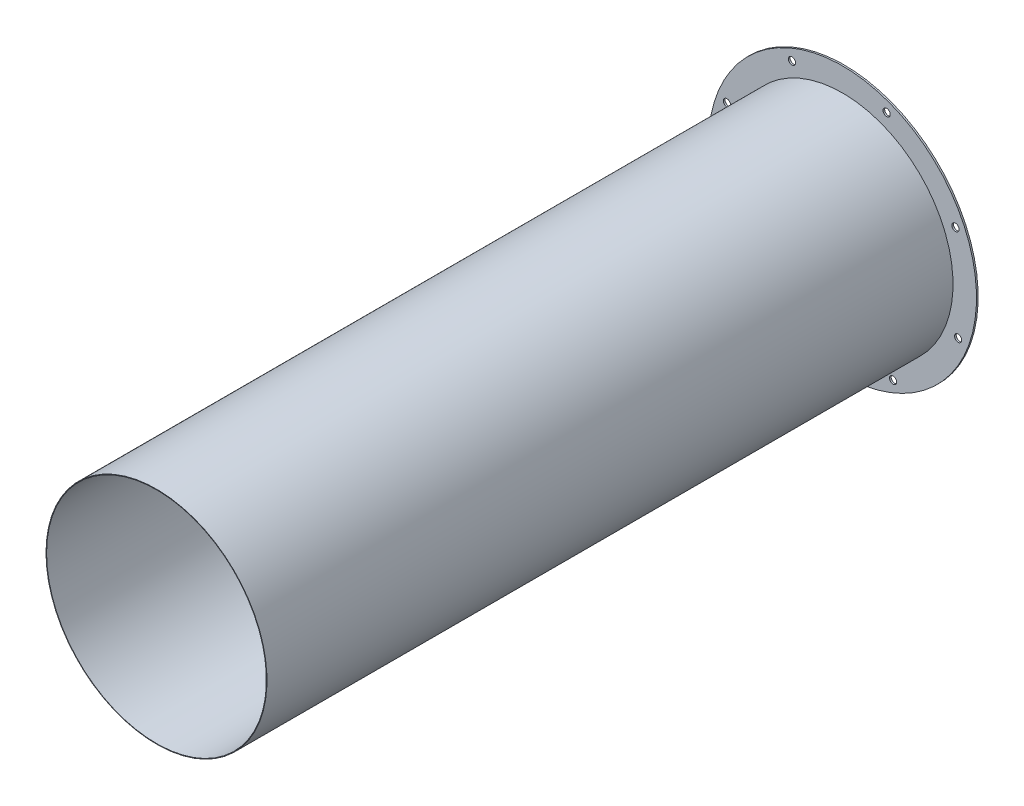
SolidWorks part; units mm, degrees
material "Galvanized Steel"
ref_plane "Front Plane" through (0, 0, 0) normal (0, 0, 1) x (1, 0, 0)
ref_plane "Top Plane" through (0, 0, 0) normal (0, 1, 0) x (1, 0, 0)
ref_plane "Right Plane" through (0, 0, 0) normal (1, 0, 0) x (0, 0, -1)
sketch "Sketch1" plane through (0, 0, 0) normal (0, 0, 1) x (1, 0, 0)
  circle A0 centre (0, 0) radius 200
  dimension "D1" = 400
extrude "Extrude-Thin1" add sketch "Sketch1" along normal mid plane 1245 thin thin type one direction reverse wall 1
sketch "Sketch2" plane through (0, 0, -622.5) normal (0, 0, -1) x (-1, 0, 0)
  circle A0 centre (0, 0) radius 242.5
  circle A1 centre (0, 0) radius 200 construction
  circle A2 centre (0, 0) radius 200
  dimension "D1" = 485
extrude "Extrude1" add sketch "Sketch2" against normal blind 3 separate body
sketch "Sketch3" plane through (0, 0, -619.5) normal (0, 0, 1) x (1, 0, 0)
  circle A0 centre (209.2865, -79.8446) radius 6.5
  dimension "D1" = 13
extrude "Cut-Extrude1" cut sketch "Sketch3" against normal blind 3
pattern_circular "CirPattern1" count 8 over 360 about axis through (0, 0, 0) along (0, 0, 1) of "Cut-Extrude1"
